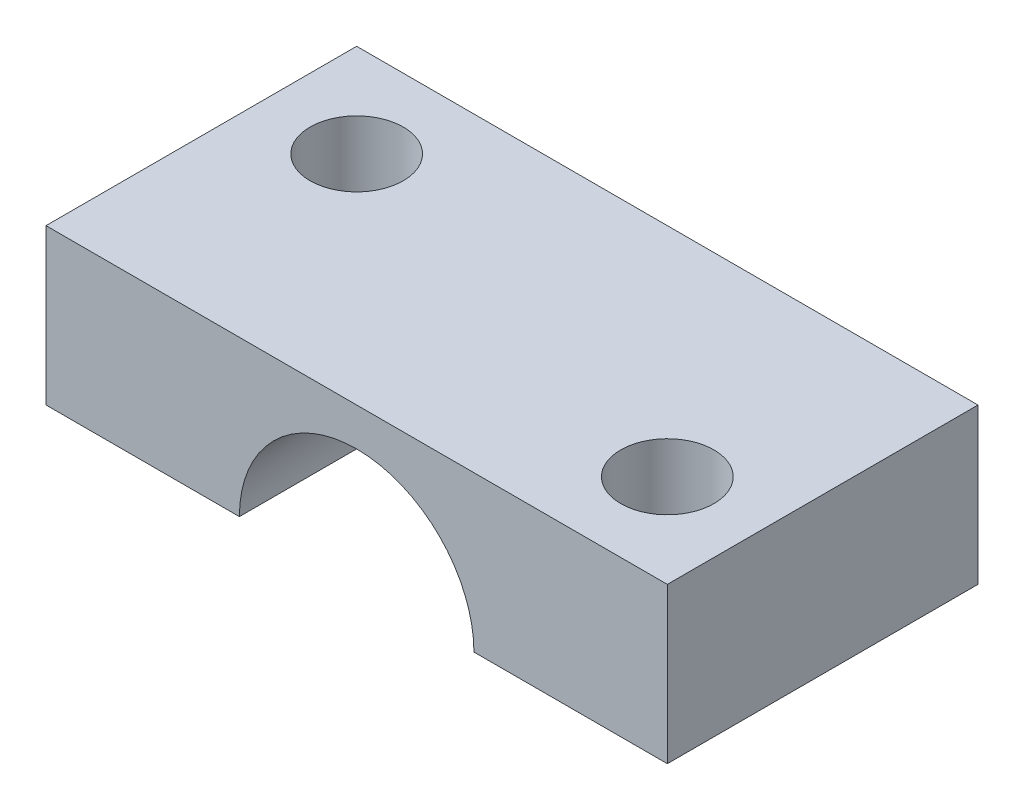
SolidWorks part; units mm, degrees
ref_plane "Front Plane" through (0, 0, 0) normal (0, 0, 1) x (1, 0, 0)
ref_plane "Top Plane" through (0, 0, 0) normal (0, 1, 0) x (1, 0, 0)
ref_plane "Right Plane" through (0, 0, 0) normal (1, 0, 0) x (0, 0, -1)
sketch "Sketch1" plane through (0, 0, 0) normal (0, 1, 0) x (1, 0, 0)
  line L1 (-25.0162, -10.246) -> (-5.0162, -10.246)
  line L2 (-25.0162, -10.246) -> (-25.0162, -0.246)
  line L3 (-25.0162, -0.246) -> (-5.0162, -0.246)
  line L4 (-5.0162, -10.246) -> (-5.0162, -0.246)
  dimension "D1" = 10
  dimension "D2" = 20
extrude "Boss-Extrude1" add sketch "Sketch1" along normal blind 5
sketch "Sketch2" plane through (0, 0, 10.246) normal (0, 0, 1) x (1, 0, 0)
  line L0 (-25.0162, 0) -> (-5.0162, 0) construction
  line L1 (-5.0162, 5) -> (-5.0162, 0) construction
  circle A0 centre (-15.0162, 0) radius 3.775
  dimension "D1" = 7.55
  dimension "D2" = 0
  dimension "D3" = 10
extrude "Cut-Extrude1" cut sketch "Sketch2" against normal blind 10
sketch "Sketch3" plane through (0, 5, 0) normal (0, 1, 0) x (1, 0, 0)
  line L0 (-25.0162, -0.246) -> (-25.0162, -10.246) construction
  line L2 (-5.0162, -0.246) -> (-25.0162, -0.246) construction
  line L3 (-5.0162, -10.246) -> (-5.0162, -0.246) construction
  line L4 (-25.0162, -10.246) -> (-5.0162, -10.246) construction
  circle A0 centre (-22.0162, -3.246) radius 1.5
  circle A1 centre (-8.0162, -7.246) radius 1.5
  dimension "D1" = 3
  dimension "D2" = 3
  dimension "D3" = 3
  dimension "D4" = 3
  dimension "D5" = 3
  dimension "D6" = 3
extrude "Cut-Extrude2" cut sketch "Sketch3" against normal blind 5
